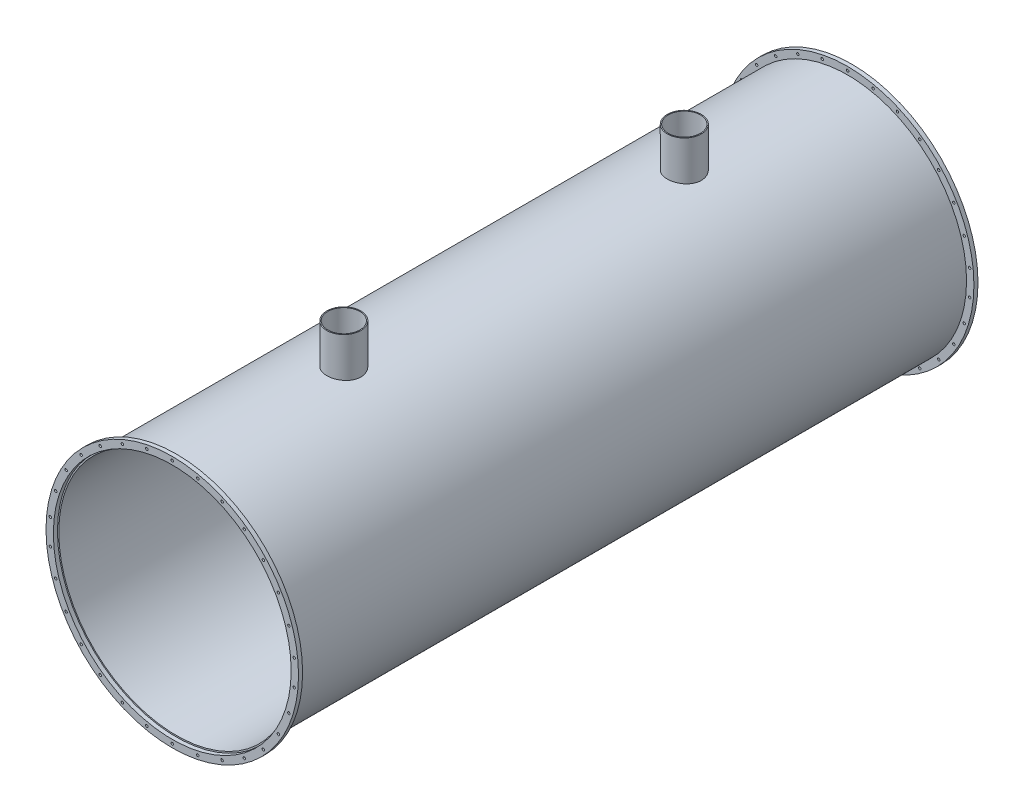
SolidWorks part; units mm, degrees
ref_plane "Front Plane" through (0, 0, 0) normal (0, 0, 1) x (1, 0, 0)
ref_plane "Top Plane" through (0, 0, 0) normal (0, 1, 0) x (1, 0, 0)
ref_plane "Right Plane" through (0, 0, 0) normal (1, 0, 0) x (0, 0, -1)
sketch "Sketch1" plane through (0, 0, 0) normal (0, 0, 1) x (1, 0, 0)
  circle A0 centre (0, 0) radius 2130.025
  circle A1 centre (0, 0) radius 2105.58
  dimension "D1" = 4260.05
  dimension "D2" = 4211.16
extrude "Boss-Extrude1" add sketch "Sketch1" along normal blind 12100
ref_plane "Plane1" through (0, 2830.0235, 0) normal (0, 1, 0) x (1, 0, 0)
sketch "Sketch2" plane through (0, 2830.0235, 0) normal (0, 1, 0) x (1, 0, 0)
  line L0 (2105.58, 0) -> (-2105.58, 0) construction
  line L1 (-2130.025, -12100) -> (2130.025, -12100) construction
  circle A0 centre (0, -3000) radius 304.8
  circle A1 centre (0, -9100) radius 304.8
  dimension "D1" = 609.6
  dimension "D2" = 3000
  dimension "D3" = 3000
extrude "Boss-Extrude2" add sketch "Sketch2" against normal up to surface up to face at (2130.025, 0, 12100)
sketch "Sketch3" plane through (0, 2830.0235, 0) normal (0, 1, 0) x (1, 0, 0)
  circle A0 centre (0, -3000) radius 287.4
  circle A1 centre (0, -9100) radius 287.4
  dimension "D1" = 574.8
extrude "Cut-Extrude1" cut sketch "Sketch3" against normal blind 1000
sketch "Sketch4" plane through (0, 0, 12100) normal (0, 0, 1) x (1, 0, 0)
  circle A0 centre (0, 0) radius 2262.0235
  circle A1 centre (0, 0) radius 2130.025 construction
  circle A2 centre (0, 0) radius 2130.025
  dimension "D1" = 4524.047
extrude "Boss-Extrude3" add sketch "Sketch4" along normal blind 73 separate body
sketch "Sketch5" plane through (0, 0, 12173) normal (0, 0, 1) x (1, 0, 0)
  circle A0 centre (0, 0) radius 2196.025 construction
  circle A1 centre (0, 2196.025) radius 22
  circle A2 centre (456.5793, 2148.0366) radius 22
  circle A3 centre (893.2038, 2006.1687) radius 22
  circle A4 centre (1290.7911, 1776.6215) radius 22
  circle A5 centre (1631.9646, 1469.4275) radius 22
  circle A6 centre (1901.8134, 1098.0125) radius 22
  circle A7 centre (2088.5439, 678.609) radius 22
  circle A8 centre (2183.9949, 229.5471) radius 22
  circle A9 centre (2183.9949, -229.5471) radius 22
  circle A10 centre (2088.5439, -678.609) radius 22
  circle A11 centre (1901.8134, -1098.0125) radius 22
  circle A12 centre (1631.9646, -1469.4275) radius 22
  circle A13 centre (1290.7911, -1776.6215) radius 22
  circle A14 centre (893.2038, -2006.1687) radius 22
  circle A15 centre (456.5793, -2148.0366) radius 22
  circle A16 centre (0, -2196.025) radius 22
  circle A17 centre (-456.5793, -2148.0366) radius 22
  circle A18 centre (-893.2038, -2006.1687) radius 22
  circle A19 centre (-1290.7911, -1776.6215) radius 22
  circle A20 centre (-1631.9646, -1469.4275) radius 22
  circle A21 centre (-1901.8134, -1098.0125) radius 22
  circle A22 centre (-2088.5439, -678.609) radius 22
  circle A23 centre (-2183.9949, -229.5471) radius 22
  circle A24 centre (-2183.9949, 229.5471) radius 22
  circle A25 centre (-2088.5439, 678.609) radius 22
  circle A26 centre (-1901.8134, 1098.0125) radius 22
  circle A27 centre (-1631.9646, 1469.4275) radius 22
  circle A28 centre (-1290.7911, 1776.6215) radius 22
  circle A29 centre (-893.2038, 2006.1687) radius 22
  circle A30 centre (-456.5793, 2148.0366) radius 22
  point P66 (0, 0)
  dimension "D1" = 4392.05
  dimension "D2" = 44
  dimension "D3" = 30
extrude "Cut-Extrude2" cut sketch "Sketch5" against normal up to next (73 mm away)
sketch "Sketch6" plane through (0, 0, 0) normal (0, 0, -1) x (-1, 0, 0)
  circle A1 centre (0, 0) radius 2130.025
  circle A2 centre (0, 0) radius 2130.025
  circle A3 centre (0, 0) radius 2262.0235
  circle A4 centre (0, 0) radius 2262.0235
  dimension "D1" = 0
  dimension "D2" = 0
extrude "Boss-Extrude4" add sketch "Sketch6" against normal blind 73
sketch "Sketch7" plane through (0, 0, 0) normal (0, 0, -1) x (-1, 0, 0)
  circle A1 centre (-1631.9646, 1469.4275) radius 22
  circle A2 centre (-1631.9646, 1469.4275) radius 22
  circle A3 centre (-1290.7911, 1776.6215) radius 22
  circle A4 centre (-1290.7911, 1776.6215) radius 22
  circle A5 centre (-893.2038, 2006.1687) radius 22
  circle A6 centre (-893.2038, 2006.1687) radius 22
  circle A7 centre (-456.5793, 2148.0366) radius 22
  circle A8 centre (-456.5793, 2148.0366) radius 22
  circle A9 centre (0, 2196.025) radius 22
  circle A10 centre (0, 2196.025) radius 22
  circle A11 centre (-1290.7911, -1776.6215) radius 22
  circle A12 centre (-1290.7911, -1776.6215) radius 22
  circle A13 centre (-1631.9646, -1469.4275) radius 22
  circle A14 centre (-1631.9646, -1469.4275) radius 22
  circle A15 centre (-1901.8134, -1098.0125) radius 22
  circle A16 centre (-1901.8134, -1098.0125) radius 22
  circle A17 centre (-2088.5439, -678.609) radius 22
  circle A18 centre (-2088.5439, -678.609) radius 22
  circle A19 centre (-2183.9949, -229.5471) radius 22
  circle A20 centre (-2183.9949, -229.5471) radius 22
  circle A21 centre (-2183.9949, 229.5471) radius 22
  circle A22 centre (-2183.9949, 229.5471) radius 22
  circle A23 centre (-2088.5439, 678.609) radius 22
  circle A24 centre (-2088.5439, 678.609) radius 22
  circle A25 centre (-1901.8134, 1098.0125) radius 22
  circle A26 centre (-1901.8134, 1098.0125) radius 22
  circle A27 centre (1901.8134, -1098.0125) radius 22
  circle A28 centre (1901.8134, -1098.0125) radius 22
  circle A29 centre (1631.9646, -1469.4275) radius 22
  circle A30 centre (1631.9646, -1469.4275) radius 22
  circle A31 centre (1290.7911, -1776.6215) radius 22
  circle A32 centre (1290.7911, -1776.6215) radius 22
  circle A33 centre (893.2038, -2006.1687) radius 22
  circle A34 centre (893.2038, -2006.1687) radius 22
  circle A35 centre (456.5793, -2148.0366) radius 22
  circle A36 centre (456.5793, -2148.0366) radius 22
  circle A37 centre (0, -2196.025) radius 22
  circle A38 centre (0, -2196.025) radius 22
  circle A39 centre (-456.5793, -2148.0366) radius 22
  circle A40 centre (-456.5793, -2148.0366) radius 22
  circle A41 centre (-893.2038, -2006.1687) radius 22
  circle A42 centre (-893.2038, -2006.1687) radius 22
  circle A43 centre (893.2038, 2006.1687) radius 22
  circle A44 centre (893.2038, 2006.1687) radius 22
  circle A45 centre (1290.7911, 1776.6215) radius 22
  circle A46 centre (1290.7911, 1776.6215) radius 22
  circle A47 centre (1631.9646, 1469.4275) radius 22
  circle A48 centre (1631.9646, 1469.4275) radius 22
  circle A49 centre (1901.8134, 1098.0125) radius 22
  circle A50 centre (1901.8134, 1098.0125) radius 22
  circle A51 centre (2088.5439, 678.609) radius 22
  circle A52 centre (2088.5439, 678.609) radius 22
  circle A53 centre (2183.9949, 229.5471) radius 22
  circle A54 centre (2183.9949, 229.5471) radius 22
  circle A55 centre (2183.9949, -229.5471) radius 22
  circle A56 centre (2183.9949, -229.5471) radius 22
  circle A57 centre (2088.5439, -678.609) radius 22
  circle A58 centre (2088.5439, -678.609) radius 22
  circle A59 centre (456.5793, 2148.0366) radius 22
  circle A60 centre (456.5793, 2148.0366) radius 22
  dimension "D1" = 0
  dimension "D2" = 0
  dimension "D3" = 0
  dimension "D4" = 0
  dimension "D5" = 0
  dimension "D6" = 0
  dimension "D7" = 0
  dimension "D8" = 0
  dimension "D9" = 0
  dimension "D10" = 0
  dimension "D11" = 0
  dimension "D12" = 0
  dimension "D13" = 0
  dimension "D14" = 0
  dimension "D15" = 0
  dimension "D16" = 0
  dimension "D17" = 0
  dimension "D18" = 0
  dimension "D19" = 0
  dimension "D20" = 0
  dimension "D21" = 0
  dimension "D22" = 0
  dimension "D23" = 0
  dimension "D24" = 0
  dimension "D25" = 0
  dimension "D26" = 0
  dimension "D27" = 0
  dimension "D28" = 0
  dimension "D29" = 0
  dimension "D30" = 0
extrude "Cut-Extrude3" cut sketch "Sketch7" against normal up to next (73 mm away)
